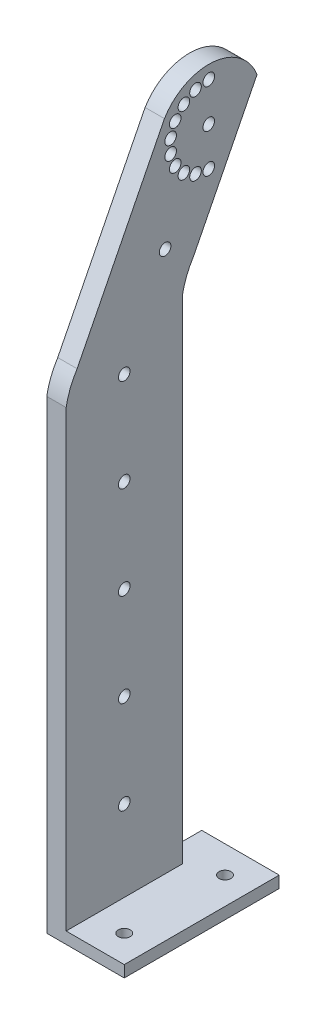
SolidWorks part; units mm, degrees
ref_plane "前视基准面" through (0, 0, 0) normal (0, 0, 1) x (1, 0, 0)
ref_plane "上视基准面" through (0, 0, 0) normal (0, 1, 0) x (1, 0, 0)
ref_plane "右视基准面" through (0, 0, 0) normal (1, 0, 0) x (0, 0, -1)
sketch "草图1" plane through (0, 0, 0) normal (1, 0, 0) x (0, 0, -1)
  line L0 (-15, 0) -> (15, 0)
  line L1 (-15, 0) -> (-15, 120)
  line L2 (15, 0) -> (15, 130)
  line L3 (17.8333, 137.2485) -> (34.2776, 169.8061)
  line L4 (-12.1667, 127.2485) -> (10.3753, 171.8787)
  line L5 (13.1525, 169.9179) -> (21.8127, 164.9179) construction
  line L7 (11.218, 143.9417) -> (10.5417, 142.6028) construction
  line L8 (21.8127, 164.9179) -> (15.3848, 172.5784) construction
  line L9 (21.8127, 164.9179) -> (11.9646, 166.6544) construction
  line L10 (11.9646, 163.1814) -> (21.8127, 164.9179) construction
  line L11 (21.8127, 164.9179) -> (18.3925, 155.521) construction
  line L12 (21.8127, 164.9179) -> (21.8127, 154.9179) construction
  line L13 (18.3925, 174.3148) -> (21.8127, 164.9179) construction
  line L14 (21.8127, 164.9179) -> (13.1525, 159.9179) construction
  line L15 (21.8127, 164.9179) -> (21.8127, 174.9179) construction
  line L16 (15.3848, 157.2575) -> (21.8127, 164.9179) construction
  arc A0 (15, 130) -> (17.8333, 137.2485) centre (34.6882, 126.4823) cw
  arc A1 (-12.1667, 127.2485) -> (-15, 120) centre (4.6882, 116.4823) ccw
  circle A2 centre (0, 23.9341) radius 1.5
  circle A3 centre (0, 47.9341) radius 1.5
  circle A4 centre (0, 71.9341) radius 1.5
  circle A5 centre (0, 95.9341) radius 1.5
  circle A7 centre (21.8127, 164.9179) radius 10 construction
  circle A8 centre (10.5417, 142.6028) radius 1.5
  circle A9 centre (0, 119.9341) radius 1.5
  arc A10 (34.2776, 169.8061) -> (10.3753, 171.8787) centre (21.8127, 164.9179) ccw
  circle A11 centre (21.8127, 164.9179) radius 1.5
  circle A13 centre (11.9646, 166.6544) radius 1.5
  circle A14 centre (11.9646, 163.1814) radius 1.5
  circle A15 centre (13.1525, 159.9179) radius 1.5
  circle A16 centre (15.3848, 157.2575) radius 1.5
  circle A19 centre (21.8127, 154.9179) radius 1.5
  circle A20 centre (18.3925, 155.521) radius 1.5
  circle A21 centre (13.1525, 169.9179) radius 1.5
  circle A22 centre (15.3848, 172.5784) radius 1.5
  circle A23 centre (18.3925, 174.3148) radius 1.5
  circle A24 centre (21.8127, 174.9179) radius 1.5
  point P3 (0, 0)
  dimension "D5" = 20
  dimension "D7" = 20
  dimension "D4" = 3
  dimension "D9" = 3
  dimension "D11" = 3
  dimension "D16" = 20
  dimension "D20" = 20
  dimension "D22" = 20
  dimension "D24" = 20
  dimension "D1" = 30
  dimension "D2" = 120
  dimension "D3" = 130
  dimension "D6" = 24
  dimension "D8" = 25
  dimension "D12" = 25
  dimension "D10" = 15
  dimension "D13" = 24
  dimension "D14" = 24
  dimension "D15" = 24
  dimension "D17" = 20
  dimension "D18" = 20
  dimension "D19" = 20
  dimension "D21" = 20
  dimension "D23" = 20
extrude "凸台-拉伸2" add sketch "草图1" against normal blind 5
ref_plane "基准面1" through (-5, 0, 0) normal (-1, 0, 0) x (0, 0, 1)
sketch "草图3" plane through (-5, 0, 0) normal (-1, 0, 0) x (0, 0, 1)
  line L25 (-10, 5) -> (10, 5)
  line L26 (-10, 130.4183) -> (-10, 5)
  line L27 (10, 5) -> (10, 119.5247)
  line L28 (-28.6572, 169.7687) -> (-13.4775, 139.7151)
  line L29 (7.8255, 124.7531) -> (-14.7389, 169.4276)
  line L30 (-10, 5) -> (10, 5)
  line L31 (-10, 130.4183) -> (-10, 5)
  line L32 (10, 5) -> (10, 119.5247)
  line L33 (-28.6572, 169.7687) -> (-13.4775, 139.7151)
  line L34 (7.8255, 124.7531) -> (-14.7389, 169.4276)
  arc A19 (10, 119.5247) -> (7.8255, 124.7531) centre (-4.6882, 116.4823) ccw
  arc A20 (-10, 130.4183) -> (-13.4775, 139.7151) centre (-34.6882, 126.4823) ccw
  arc A21 (-14.7389, 169.4276) -> (-28.6572, 169.7687) centre (-21.8127, 164.9179) ccw
  arc A22 (10, 119.5247) -> (7.8255, 124.7531) centre (-4.6882, 116.4823) ccw
  arc A23 (-10, 130.4183) -> (-13.4775, 139.7151) centre (-34.6882, 126.4823) ccw
  arc A24 (-14.7389, 169.4276) -> (-28.6572, 169.7687) centre (-21.8127, 164.9179) ccw
  dimension "D1" = 5
extrude "切除-拉伸2" cut sketch "草图3" against normal blind 1
ref_plane "基准面3" through (-30, 0, 0) normal (-1, 0, 0) x (0, 0, 1)
ref_plane "基准面4" through (0, 0, 0) normal (0, -1, 0) x (-1, 0, 0)
sketch "草图4" plane through (0, 0, 0) normal (0, -1, 0) x (-1, 0, 0)
  line L0 (5, -15) -> (-15, -15)
  line L1 (5, -15) -> (0, -15) construction
  line L2 (-15, -15) -> (-15, 25)
  line L3 (-15, 25) -> (5, 25)
  line L4 (5, 25) -> (5, -15)
  line L5 (5, -15) -> (5, 15) construction
  dimension "D1" = 20
  dimension "D2" = 40
  dimension "D3" = 20
extrude "凸台-拉伸3" add sketch "草图4" against normal blind 3
sketch "草图5" plane through (0, 0, 0) normal (0, -1, 0) x (1, 0, 0)
  line L0 (-5, -25) -> (15, -25) construction
  line L2 (15, -25) -> (15, 15) construction
  line L3 (-5, 15) -> (15, 15) construction
  circle A0 centre (8, -18) radius 1.55
  circle A1 centre (8, 8) radius 1.55
  dimension "D1" = 3.1
  dimension "D4" = 3.1
  dimension "D2" = 7
  dimension "D3" = 7
  dimension "D5" = 7
extrude "切除-拉伸3" cut sketch "草图5" against normal blind 10
